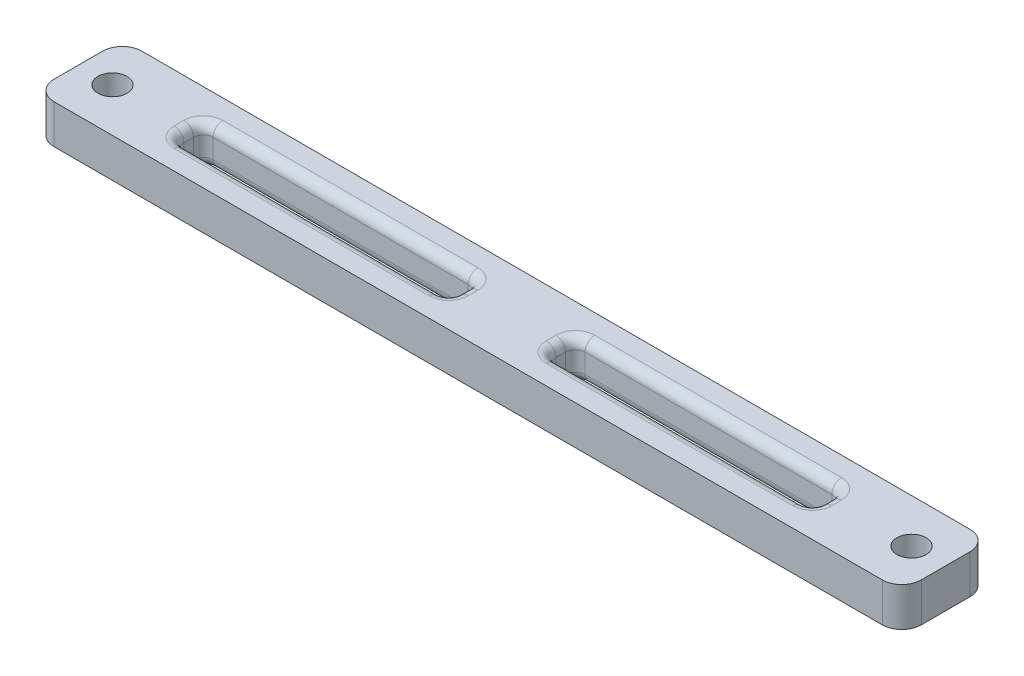
SolidWorks part; units mm, degrees
ref_plane "Front Plane" through (0, 0, 0) normal (0, 0, 1) x (1, 0, 0)
ref_plane "Top Plane" through (0, 0, 0) normal (0, 1, 0) x (1, 0, 0)
ref_plane "Right Plane" through (0, 0, 0) normal (1, 0, 0) x (0, 0, -1)
sketch "Sketch1" plane through (0, 0, 0) normal (0, 1, 0) x (1, 0, 0)
  line L1 (44.5, 4.5) -> (-44.5, 4.5)
  line L2 (44.5, 4.5) -> (44.5, -4.5)
  line L3 (44.5, -4.5) -> (-44.5, -4.5)
  line L4 (-44.5, 4.5) -> (-44.5, -4.5)
  line L5 (44.5, 4.5) -> (-44.5, -4.5) construction
  line L6 (44.5, -4.5) -> (-44.5, 4.5) construction
  point P0 (0, 0)
  dimension "D1" = 89
  dimension "D2" = 9
extrude "Boss-Extrude1" add sketch "Sketch1" along normal blind 4
sketch "Sketch2" plane through (0, 4, 0) normal (0, 1, 0) x (1, 0, 0)
  circle A0 centre (-41, 0) radius 1.5
  circle A1 centre (41, 0) radius 1.5
  dimension "D3" = 3
  dimension "D4" = 3
  dimension "D1" = 41
  dimension "D2" = 41
extrude "Cut-Extrude1" cut sketch "Sketch2" against normal blind 4
fillet "Fillet1" radius 2 4 edges at (44.5, 2, -4.5) (44.5, 2, 4.5) (-44.5, 2, -4.5) (-44.5, 2, 4.5)
sketch "Sketch4" plane through (0, 4, 0) normal (0, 1, 0) x (1, 0, 0)
  line L0 (42.5, 4.5) -> (-42.5, 4.5) construction
  line L1 (-33.1754, 1.5) -> (-5, 1.5)
  line L2 (-33.1754, 1.5) -> (-33.1754, -1.5)
  line L3 (-33.1754, -1.5) -> (-5, -1.5)
  line L4 (32.3159, 1.5) -> (32.3159, -1.5)
  line L5 (-42.5, -4.5) -> (42.5, -4.5) construction
  line L6 (-5, 1.5) -> (-5, -1.5)
  line L7 (5, 1.5) -> (5, -1.5)
  line L8 (5, 1.5) -> (32.3159, 1.5)
  line L9 (5, -1.5) -> (32.3159, -1.5)
  dimension "D1" = 3
  dimension "D2" = 3
  dimension "D3" = 10
  dimension "D4" = 5
extrude "Cut-Extrude2" cut sketch "Sketch4" against normal through all
fillet "Fillet3" radius 1 24 edges at (-33.1754, 2, 1.5) (-33.1754, 2, -1.5) (18.658, 0, -1.5) (18.658, 4, -1.5) (18.658, 0, 1.5) (18.658, 4, 1.5) (-19.0877, 0, 1.5) (-19.0877, 4, 1.5) (-19.0877, 0, -1.5) (-19.0877, 4, -1.5) (5, 2, -1.5) (5, 2, 1.5) (-5, 2, 1.5) (-5, 2, -1.5) (32.3159, 2, 1.5) (32.3159, 2, -1.5) (32.3159, 0, 0) (32.3159, 4, 0) (-33.1754, 0, 0) (-33.1754, 4, 0) (5, 0, 0) (5, 4, 0) (-5, 0, 0) (-5, 4, 0)
